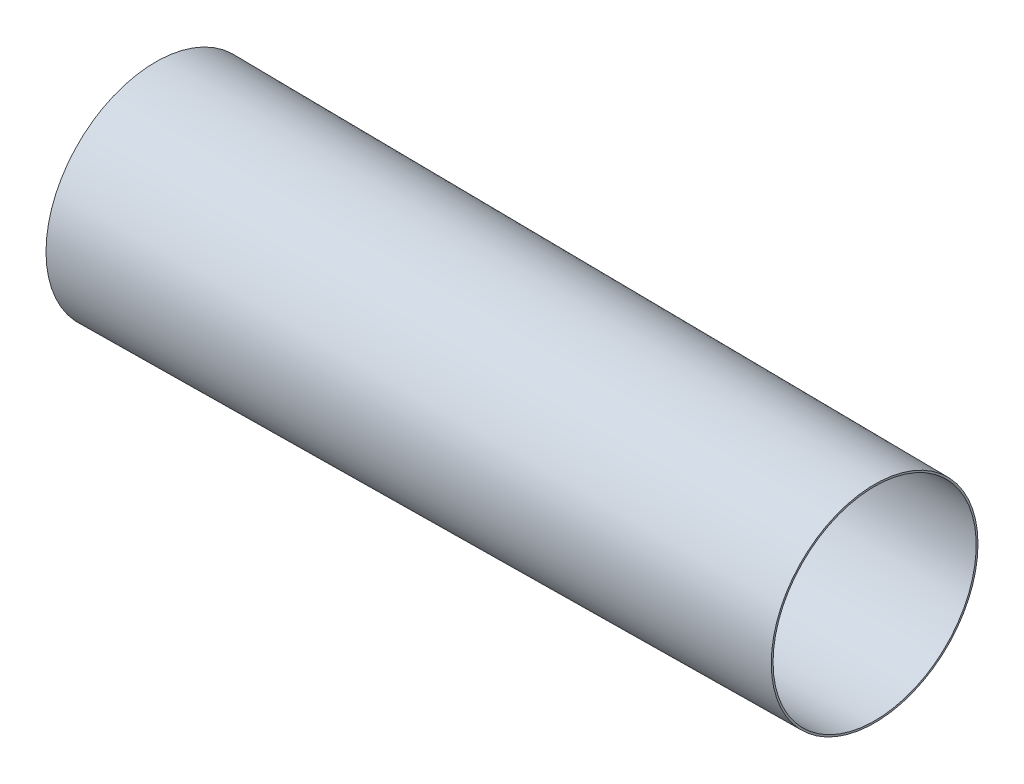
SolidWorks part; units mm, degrees
ref_plane "Ebene vorne" through (0, 0, 0) normal (0, 0, 1) x (1, 0, 0)
ref_plane "Ebene oben" through (0, 0, 0) normal (0, 1, 0) x (1, 0, 0)
ref_plane "Ebene rechts" through (0, 0, 0) normal (1, 0, 0) x (0, 0, -1)
sketch "Skizze1" plane through (0, 0, 0) normal (0, 1, 0) x (1, 0, 0)
  line L0 (0, -60) -> (0, 60) construction
  line L1 (0, 60) -> (400, 56.5093)
  line L2 (400, 56.5093) -> (400, 57.5093)
  line L3 (400, 57.5093) -> (0, 61)
  line L4 (0, 61) -> (0, 60)
  line L5 (0, 60) -> (400, 60) construction
  line L6 (400, 56.5093) -> (400, 60) construction
  line L7 (0, 0) -> (400, 0) construction
  line L8 (0, 61) -> (-1, 61) construction
  line L9 (-1, 61) -> (-1, 0) construction
  line L10 (-1, 0) -> (0, 0) construction
  line L11 (0, 0) -> (0, 60) construction
  line L12 (400, 57.5093) -> (401, 57.5093) construction
  line L13 (401, 57.5093) -> (401, 0) construction
  line L14 (401, 0) -> (400, 0) construction
  line L15 (400, 0) -> (400, 56.5093) construction
  point P4 (0, 0)
  dimension "D2" = 1
  dimension "D3" = 400
  dimension "D4" = 120
  dimension "D5" = 1
  dimension "D6" = 1
  dimension "D7" = 89.5
revolve "Rotation1" add sketch "Skizze1" angle 360 about L7
equation "\"angle\" = - 0.5"
equation "\"length\"= 400"
equation "\"D3@Skizze1\"=\"length\""
equation "\"dia_inner\"= 120"
equation "\"D4@Skizze1\"=\"dia_inner\""
equation "\"D7@Skizze1\"=90 + \"angle\""
